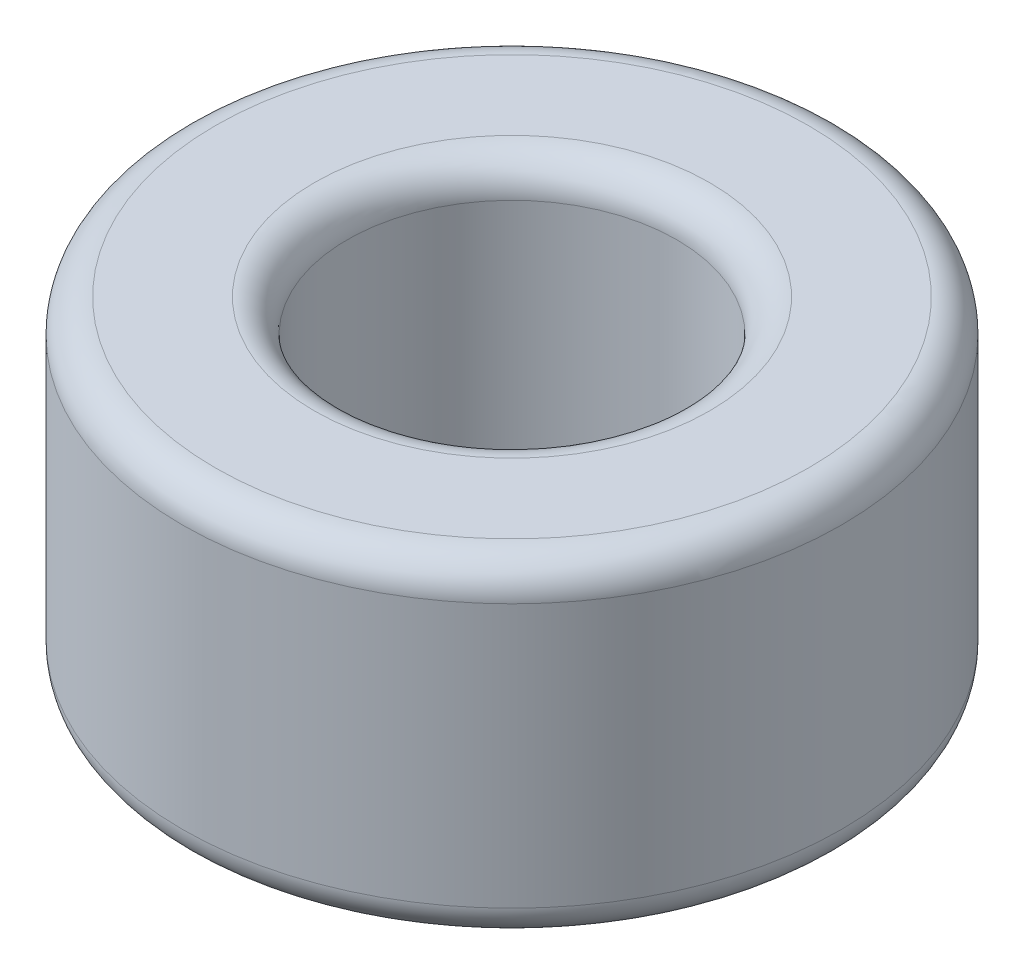
SolidWorks part; units mm, degrees
material "PUR"
ref_plane "Plano frontal" through (0, 0, 0) normal (0, 0, 1) x (1, 0, 0)
ref_plane "Plano superior" through (0, 0, 0) normal (0, 1, 0) x (1, 0, 0)
ref_plane "Plano direito" through (0, 0, 0) normal (1, 0, 0) x (0, 0, -1)
sketch "Esboço1" plane through (0, 0, 0) normal (1, 0, 0) x (0, 0, -1)
  line L7 (0, 0) -> (0, -12633.3702) construction
  line L9 (-4.5, 2.5) -> (-3, 2.5)
  line L10 (-5, 2) -> (-5, -2)
  line L11 (-4.5, -2.5) -> (-3, -2.5)
  line L12 (-2.5, 2) -> (-2.5, -2)
  arc A1 (-5, -2) -> (-4.5, -2.5) centre (-4.5, -2) ccw
  arc A2 (-3, -2.5) -> (-2.5, -2) centre (-3, -2) ccw
  arc A3 (-3, 2.5) -> (-2.5, 2) centre (-3, 2) cw
  arc A4 (-4.5, 2.5) -> (-5, 2) centre (-4.5, 2) ccw
  point P5 (-2.5, 0)
  point P8 (-5, -2.5)
  point P18 (-5, 2.5)
  dimension "D4" = 0.5
  dimension "D1" = 5
  dimension "D2" = 10
  dimension "D3" = 5
revolve "Revolução1" add sketch "Esboço1" angle 360 about L7
